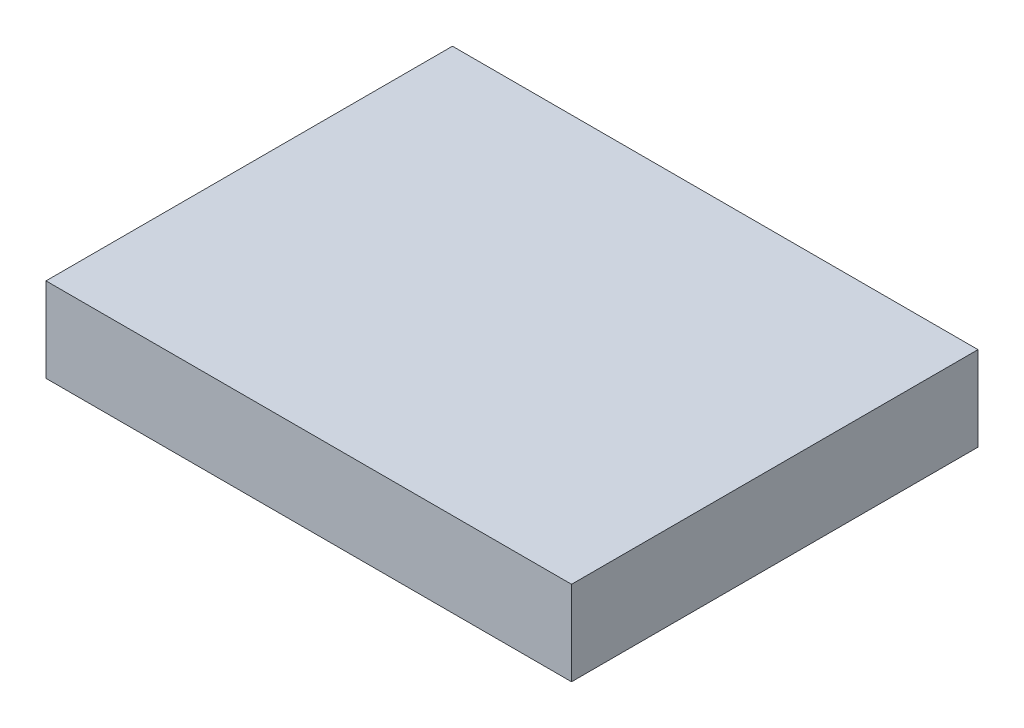
SolidWorks part; units mm, degrees
ref_plane "Front Plane" through (0, 0, 0) normal (0, 0, 1) x (1, 0, 0)
ref_plane "Top Plane" through (0, 0, 0) normal (0, 1, 0) x (1, 0, 0)
ref_plane "Right Plane" through (0, 0, 0) normal (1, 0, 0) x (0, 0, -1)
sketch "Sketch1" plane through (0, 0, 0) normal (1, 0, 0) x (0, 0, -1)
  line L1 (-68.7535, 25.4) -> (68.7535, 25.4)
  line L2 (-68.7535, 25.4) -> (-68.7535, -3.175)
  line L3 (-68.7535, -3.175) -> (68.7535, -3.175)
  line L4 (68.7535, 25.4) -> (68.7535, -3.175)
  point P0 (0, 0)
  dimension "D1" = 3.175
  dimension "D2" = 25.4
extrude "Extrude1" add sketch "Sketch1" against normal blind 177.8
sketch "Sketch2" plane through (0, 0, 0) normal (1, 0, 0) x (0, 0, -1)
  line L0 (25.1244, 17.1842) -> (26.4396, 15.8691)
  line L1 (42.087, 15.8691) -> (43.4021, 17.1842)
  line L7 (24.1945, 35.8608) -> (44.3321, 35.8608)
  line L8 (24.1945, 35.8608) -> (24.1945, 19.4293)
  line L9 (28.6846, 14.9392) -> (39.8419, 14.9392)
  line L10 (44.3321, 35.8608) -> (44.3321, 19.4293)
  arc A0 (25.1244, 17.1842) -> (24.1945, 19.4293) centre (27.3695, 19.4293) cw
  arc A1 (26.4396, 15.8691) -> (28.6846, 14.9392) centre (28.6846, 18.1142) ccw
  arc A2 (42.087, 15.8691) -> (39.8419, 14.9392) centre (39.8419, 18.1142) cw
  arc A3 (43.4021, 17.1842) -> (44.3321, 19.4293) centre (41.1571, 19.4293) ccw
  point P0 (34.2633, 25.4)
  point P1 (34.2633, 25.4)
  point P2 (44.3321, 22.6703)
  point P4 (24.1945, 22.6703)
  point P5 (34.2633, 25.4)
  point P11 (24.1945, 18.1142)
  point P13 (24.1945, 25.8453)
  point P17 (41.1571, 14.9392)
  point P18 (41.1571, 22.6703)
  point P21 (34.2633, 25.4)
  point P22 (44.3321, 14.9392)
  point P25 (24.1945, 14.9392)
  dimension "D5" = 3.175
  dimension "D6" = 45
  dimension "D7" = 3.175
  dimension "D1" = 3.175
  dimension "D2" = 3.175
  dimension "D3" = 3.175
  dimension "D4" = 45
ref_plane "Plane1" through (0, 25.4, 0) normal (0, 1, 0) x (-1, 0, 0)
sketch "Sketch3" plane through (0, 25.4, 0) normal (0, 1, 0) x (-1, 0, 0)
  line L0 (0, -34.2633) -> (67.4966, -34.2633)
  line L2 (0, -68.7535) -> (0, 68.7535) construction
  line L3 (75.8052, -35.6606) -> (98.3925, -43.4793)
  line L4 (0, 0) -> (103.7748, 0) construction
  line L5 (75.8052, 35.6606) -> (98.3925, 43.4793)
  line L6 (0, 34.2633) -> (67.4966, 34.2633)
  arc A0 (112.2909, -44.2539) -> (112.2909, 44.2539) centre (102.307, 0) ccw
  arc A1 (98.3925, 43.4793) -> (112.2909, 44.2539) centre (106.7011, 19.4767) cw
  arc A2 (98.3925, -43.4793) -> (112.2909, -44.2539) centre (106.7011, -19.4767) ccw
  arc A3 (75.8052, 35.6606) -> (67.4966, 34.2633) centre (67.4966, 59.6633) cw
  arc A4 (67.4966, -34.2633) -> (75.8052, -35.6606) centre (67.4966, -59.6633) cw
  point P15 (103.7748, 45.3424)
  point P18 (103.7748, -45.3424)
  point P21 (71.7684, 34.2633)
  point P24 (71.7684, -34.2633)
  dimension "D1" = 25.4
